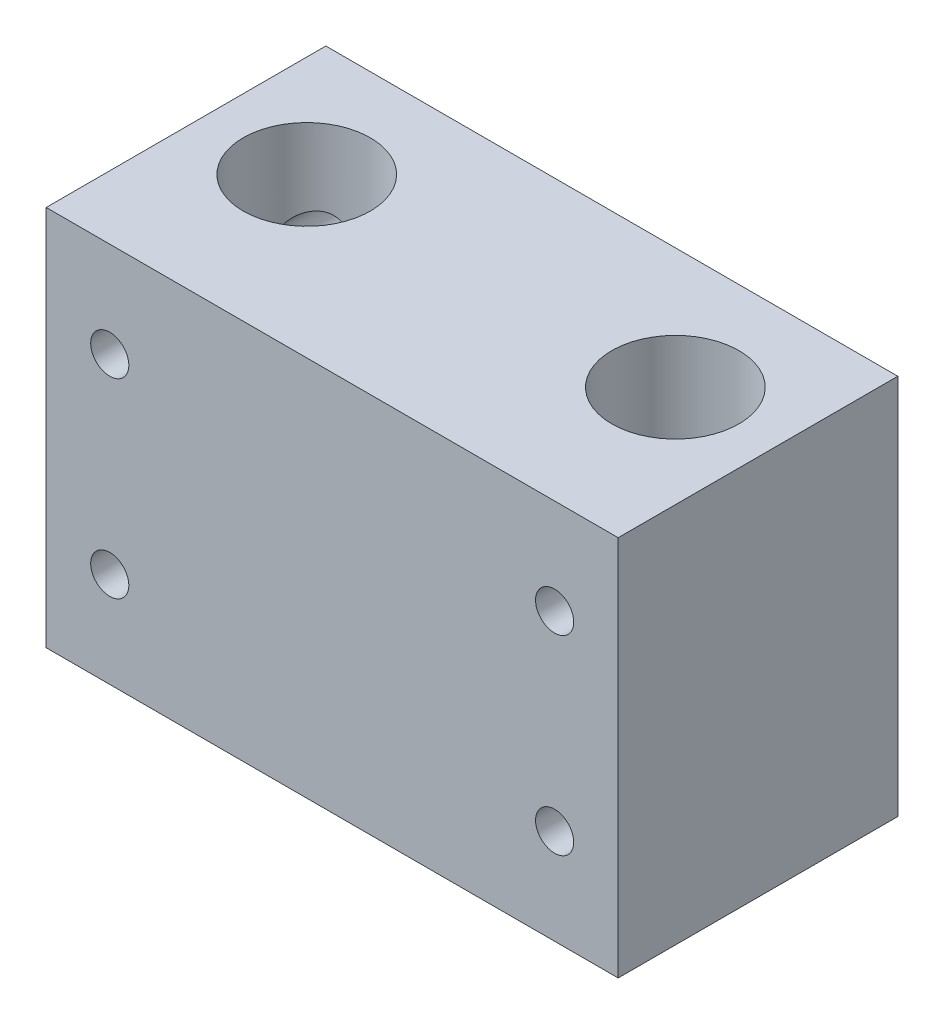
SolidWorks part; units mm, degrees
ref_plane "Front Plane" through (0, 0, 0) normal (0, 0, 1) x (1, 0, 0)
ref_plane "Top Plane" through (0, 0, 0) normal (0, 1, 0) x (1, 0, 0)
ref_plane "Right Plane" through (0, 0, 0) normal (1, 0, 0) x (0, 0, -1)
sketch "Sketch1" plane through (0, 0, 0) normal (0, 0, 1) x (1, 0, 0)
  line L1 (-22.5, 15) -> (22.5, 15)
  line L2 (-22.5, 15) -> (-22.5, -15)
  line L3 (-22.5, -15) -> (22.5, -15)
  line L4 (22.5, 15) -> (22.5, -15)
  line L5 (-22.5, 15) -> (22.5, -15) construction
  line L6 (-22.5, -15) -> (22.5, 15) construction
  point P0 (0, 0)
  dimension "D1" = 30
  dimension "D2" = 45
extrude "Boss-Extrude2" add sketch "Sketch1" along normal blind 25
sketch "Sketch4" plane through (0, 0, 0) normal (0, 0, -1) x (-1, 0, 0)
  line L1 (-17.5, 7.5) -> (17.5, 7.5)
  line L2 (-17.5, 7.5) -> (-17.5, -7.5)
  line L3 (-17.5, -7.5) -> (17.5, -7.5)
  line L4 (17.5, 7.5) -> (17.5, -7.5)
  line L5 (-17.5, 7.5) -> (17.5, -7.5) construction
  line L6 (-17.5, -7.5) -> (17.5, 7.5) construction
  circle A0 centre (-17.5, 7.5) radius 1.5
  circle A1 centre (17.5, 7.5) radius 1.5
  circle A2 centre (-17.5, -7.5) radius 1.5
  circle A3 centre (17.5, -7.5) radius 1.5
  point P0 (0, 0)
  dimension "D3" = 3
  dimension "D1" = 15
  dimension "D2" = 35
extrude "Cut-Extrude3" cut sketch "Sketch4" against normal blind 25 contours A0 | A2 | A3 | A1
sketch "Sketch5" plane through (0, 15, 0) normal (0, 1, 0) x (1, 0, 0)
  line L0 (-22.5, 0) -> (22.5, -25) construction
  line L1 (-22.5, -12.5) -> (22.5, -12.5) construction
  line L2 (-22.5, -25) -> (-22.5, 0) construction
  line L3 (22.5, -25) -> (22.5, 0) construction
  circle A0 centre (-14.5, -12.5) radius 5
  circle A1 centre (14.5, -12.5) radius 5
  dimension "D3" = 10
  dimension "D1" = 8
  dimension "D2" = 8
extrude "Cut-Extrude5" cut sketch "Sketch5" against normal through all
sketch "Sketch6" plane through (0, 0, 25) normal (0, 0, 1) x (1, 0, 0)
  line L1 (-22.5, 15) -> (22.5, 15)
  line L2 (-22.5, 15) -> (-22.5, -15)
  line L3 (-22.5, -15) -> (22.5, -15)
  line L4 (22.5, 15) -> (22.5, -15)
sketch "Sketch7" plane through (0, 0, 0) normal (0, 0, -1) x (-1, 0, 0)
  line L1 (-22.5, 15) -> (22.5, 15)
  line L2 (-22.5, 15) -> (-22.5, -15)
  line L3 (-22.5, -15) -> (22.5, -15)
  line L4 (22.5, 15) -> (22.5, -15)
extrude "Cut-Extrude8" cut sketch "Sketch7" against normal blind 3
